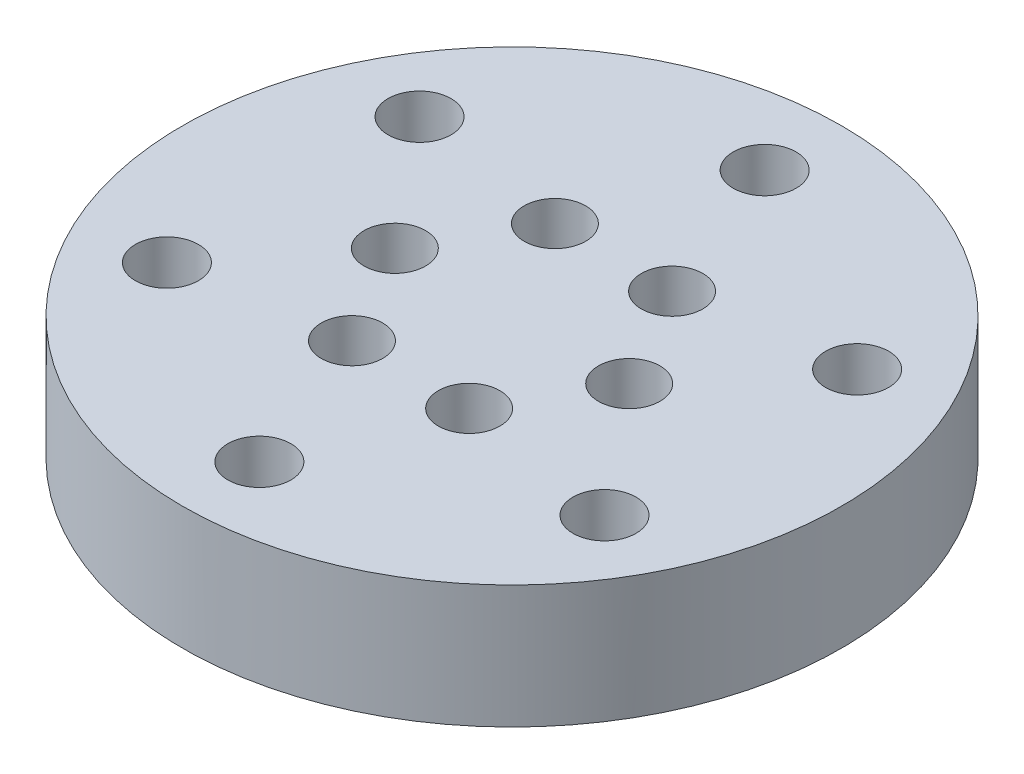
SolidWorks part; units mm, degrees
ref_plane "前视基准面" through (0, 0, 0) normal (0, 0, 1) x (1, 0, 0)
ref_plane "上视基准面" through (0, 0, 0) normal (0, 1, 0) x (1, 0, 0)
ref_plane "右视基准面" through (0, 0, 0) normal (1, 0, 0) x (0, 0, -1)
other "Configuration Table"
sketch "草图1" plane through (0, 0, 0) normal (0, 1, 0) x (1, 0, 0)
  circle A0 centre (0, 0) radius 17.25 construction
  circle A1 centre (0, 17.25) radius 2.15
  circle A2 centre (14.9389, 8.625) radius 2.15
  circle A3 centre (14.9389, -8.625) radius 2.15
  circle A4 centre (0, -17.25) radius 2.15
  circle A5 centre (-14.9389, -8.625) radius 2.15
  circle A6 centre (-14.9389, 8.625) radius 2.15
  circle A7 centre (0, 0) radius 22.5
  point P17 (0, 0)
  dimension "D1" = 34.5
  dimension "D2" = 4.3
  dimension "D4" = 45
  dimension "D3" = 6
extrude "凸台-拉伸1" add sketch "草图1" along normal blind 10.4
sketch "草图3" plane through (0, 0, 0) normal (0, -1, 0) x (1, 0, 0)
  circle A0 centre (0, 17.25) radius 4
  circle A1 centre (0, -17.25) radius 2.15
  circle A2 centre (0, -17.25) radius 2.15
  circle A3 centre (14.9389, -8.625) radius 2.15
  circle A4 centre (14.9389, -8.625) radius 2.15
  circle A5 centre (14.9389, 8.625) radius 2.15
  circle A6 centre (14.9389, 8.625) radius 2.15
  circle A7 centre (0, 17.25) radius 2.15
  circle A8 centre (0, 17.25) radius 2.15
  circle A9 centre (-14.9389, 8.625) radius 2.15
  circle A10 centre (-14.9389, 8.625) radius 2.15
  circle A11 centre (-14.9389, -8.625) radius 2.15
  circle A12 centre (-14.9389, -8.625) radius 2.15
  circle A13 centre (14.9389, 8.625) radius 4
  circle A14 centre (14.9389, -8.625) radius 4
  circle A15 centre (0, -17.25) radius 4
  circle A16 centre (-14.9389, -8.625) radius 4
  circle A17 centre (-14.9389, 8.625) radius 4
  point P32 (0, 0)
  dimension "D7" = 8
  dimension "D1" = 0
  dimension "D2" = 0
  dimension "D3" = 0
  dimension "D4" = 0
  dimension "D5" = 0
  dimension "D6" = 0
  dimension "D8" = 6
extrude "切除-拉伸1" cut sketch "草图3" against normal blind 5
sketch "草图4" plane through (0, 0, 0) normal (0, -1, 0) x (1, 0, 0)
  line L0 (0, 0) -> (0, 29.7075)
  line L1 (0, 0) -> (15.4798, 26.8119)
  circle A0 centre (4, 6.9282) radius 2.1
  circle A1 centre (8, 0) radius 2.1
  circle A2 centre (4, -6.9282) radius 2.1
  circle A3 centre (-4, -6.9282) radius 2.1
  circle A4 centre (-8, 0) radius 2.1
  circle A5 centre (-4, 6.9282) radius 2.1
  point P19 (0, 0)
  dimension "D2" = 4.2
  dimension "D1" = 30
  dimension "D3" = 8
  dimension "D4" = 6
extrude "切除-拉伸2" cut sketch "草图4" against normal through all contours L1 A0 | A1 | L1 A0 | A5 | A4 | A3 | A2
sketch "草图6" plane through (0, 0, 0) normal (0, -1, 0) x (1, 0, 0)
  circle A1 centre (0, 0) radius 22.5
  circle A2 centre (0, 0) radius 22.5
  dimension "D1" = 0
extrude "切除-拉伸3" cut sketch "草图6" against normal blind 2
sketch "草图7" plane through (0, 10.4, 0) normal (0, 1, 0) x (1, 0, 0)
  line L0 (8, 4.6188) -> (8, 9.2376)
  line L1 (0, 9.2376) -> (-4, 11.547)
  line L2 (-4, 11.547) -> (-8, 9.2376)
  line L3 (-8, 9.2376) -> (-8, 4.6188)
  line L4 (-8, 4.6188) -> (-4, 2.3094)
  line L5 (-4, 2.3094) -> (0, 4.6188)
  line L6 (0, 4.6188) -> (0, 9.2376)
  line L7 (8, 9.2376) -> (4, 11.547)
  line L8 (4, 11.547) -> (0, 9.2376)
  line L9 (0, 9.2376) -> (0, 4.6188)
  line L10 (0, 4.6188) -> (4, 2.3094)
  line L11 (4, 2.3094) -> (8, 4.6188)
  line L12 (8, -4.6188) -> (12, -2.3094)
  line L13 (12, -2.3094) -> (12, 2.3094)
  line L14 (12, 2.3094) -> (8, 4.6188)
  line L15 (8, 4.6188) -> (4, 2.3094)
  line L16 (4, 2.3094) -> (4, -2.3094)
  line L17 (4, -2.3094) -> (8, -4.6188)
  line L18 (0, -9.2376) -> (4, -11.547)
  line L19 (4, -11.547) -> (8, -9.2376)
  line L20 (8, -9.2376) -> (8, -4.6188)
  line L21 (8, -4.6188) -> (4, -2.3094)
  line L22 (4, -2.3094) -> (0, -4.6188)
  line L23 (0, -4.6188) -> (0, -9.2376)
  line L24 (-8, -4.6188) -> (-8, -9.2376)
  line L25 (-8, -9.2376) -> (-4, -11.547)
  line L26 (-4, -11.547) -> (0, -9.2376)
  line L27 (0, -9.2376) -> (0, -4.6188)
  line L28 (0, -4.6188) -> (-4, -2.3094)
  line L29 (-4, -2.3094) -> (-8, -4.6188)
  line L30 (-8, 4.6188) -> (-12, 2.3094)
  line L31 (-12, 2.3094) -> (-12, -2.3094)
  line L32 (-12, -2.3094) -> (-8, -4.6188)
  line L33 (-8, -4.6188) -> (-4, -2.3094)
  line L34 (-4, -2.3094) -> (-4, 2.3094)
  line L35 (-4, 2.3094) -> (-8, 4.6188)
  circle A0 centre (-4, 6.9282) radius 4 construction
  circle A1 centre (-14.9389, -8.625) radius 2.15
  circle A2 centre (-14.9389, -8.625) radius 2.15
  circle A3 centre (14.9389, -8.625) radius 2.15
  circle A4 centre (14.9389, -8.625) radius 2.15
  circle A5 centre (0, 17.25) radius 2.15
  circle A6 centre (0, 17.25) radius 2.15
  circle A7 centre (14.9389, 8.625) radius 2.15
  circle A8 centre (14.9389, 8.625) radius 2.15
  circle A9 centre (0, -17.25) radius 2.15
  circle A10 centre (0, -17.25) radius 2.15
  circle A11 centre (-14.9389, 8.625) radius 2.15
  circle A12 centre (-14.9389, 8.625) radius 2.15
  circle A13 centre (8, 0) radius 2.1
  circle A14 centre (8, 0) radius 2.1
  circle A15 centre (4, 6.9282) radius 2.1
  circle A16 centre (4, 6.9282) radius 2.1
  circle A17 centre (-4, 6.9282) radius 2.1
  circle A18 centre (-4, 6.9282) radius 2.1
  circle A19 centre (-8, 0) radius 2.1
  circle A20 centre (-8, 0) radius 2.1
  circle A21 centre (-4, -6.9282) radius 2.1
  circle A22 centre (-4, -6.9282) radius 2.1
  circle A23 centre (4, -6.9282) radius 2.1
  circle A24 centre (4, -6.9282) radius 2.1
  point P76 (0, 0)
  dimension "D13" = 8
  dimension "D1" = 0
  dimension "D2" = 0
  dimension "D3" = 0
  dimension "D4" = 0
  dimension "D5" = 0
  dimension "D6" = 0
  dimension "D7" = 0
  dimension "D8" = 0
  dimension "D9" = 0
  dimension "D10" = 0
  dimension "D11" = 0
  dimension "D12" = 0
  dimension "D14" = 6
extrude "切除-拉伸4" [suppressed] cut sketch "草图7" against normal blind 5
move or copy body "实体-移动/复制1" [suppressed] bodies to move or copy 110 parameters "D1"=0, "D2"=0, "D3"=0
move or copy body "实体-移动/复制2" [suppressed] bodies to move or copy 112 parameters "D1"=0, "D2"=0, "D3"=0
